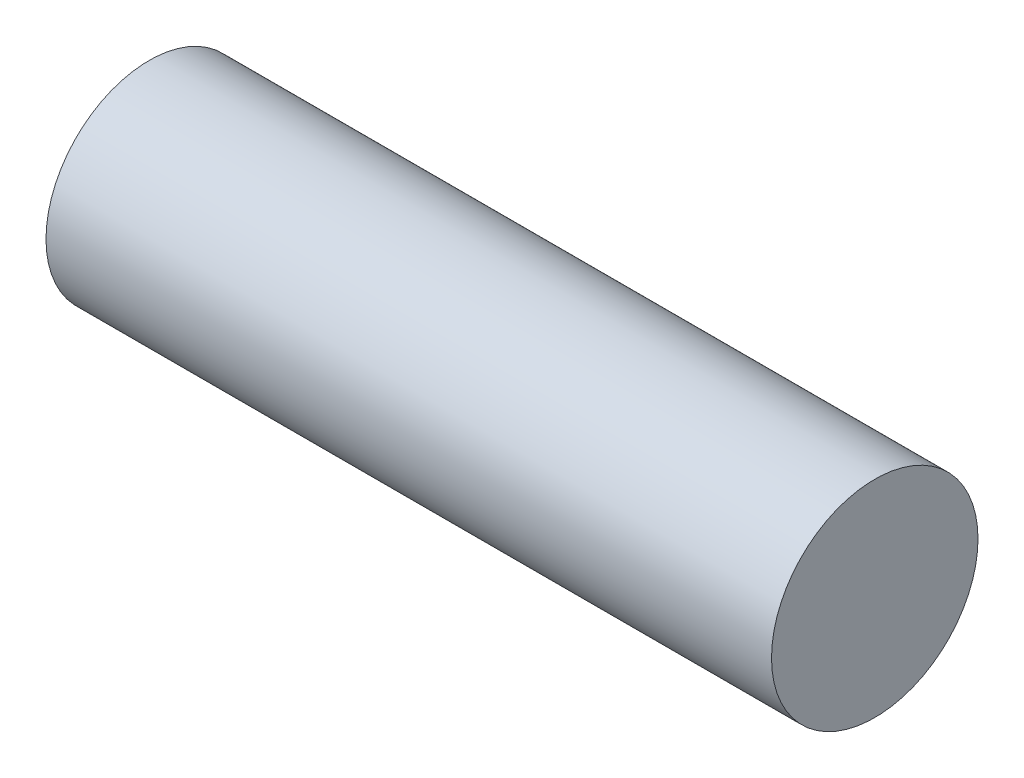
SolidWorks part; units mm, degrees
ref_plane "Front Plane" through (0, 0, 0) normal (0, 0, 1) x (1, 0, 0)
ref_plane "Top Plane" through (0, 0, 0) normal (0, 1, 0) x (1, 0, 0)
ref_plane "Right Plane" through (0, 0, 0) normal (1, 0, 0) x (0, 0, -1)
sketch "Sketch1" plane through (0, 0, 0) normal (1, 0, 0) x (0, 0, -1)
  circle A0 centre (0, 0) radius 9.25
  dimension "D1" = 18.5
extrude "Boss-Extrude1" add sketch "Sketch1" along normal mid plane 65
